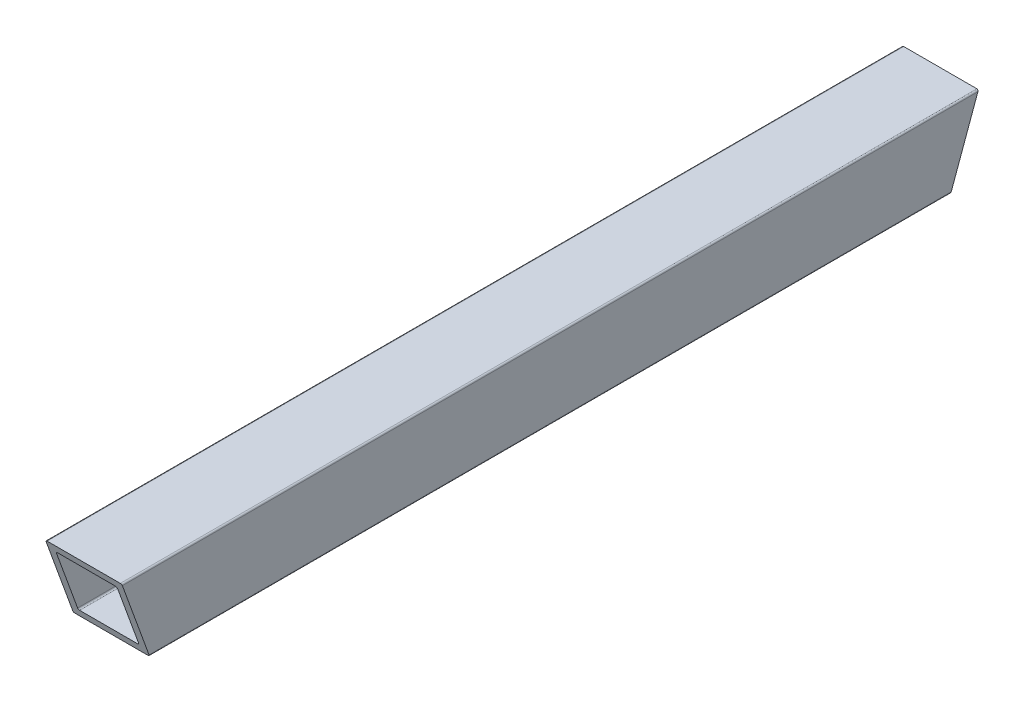
SolidWorks part; units mm, degrees
ref_plane "前基準面" through (0, 0, 0) normal (0, 0, 1) x (1, 0, 0)
ref_plane "上基準面" through (0, 0, 0) normal (0, 1, 0) x (1, 0, 0)
ref_plane "右基準面" through (0, 0, 0) normal (1, 0, 0) x (0, 0, -1)
sketch "草圖1" plane through (0, 0, 0) normal (0, 0, 1) x (1, 0, 0)
  line L1 (-5, 5) -> (5, 5)
  line L2 (-5, 5) -> (-5, -5)
  line L3 (-5, -5) -> (5, -5)
  line L4 (5, 5) -> (5, -5)
  line L5 (-4, 4) -> (4, 4)
  line L6 (-4, 4) -> (-4, -4)
  line L7 (-4, -4) -> (4, -4)
  line L8 (4, 4) -> (4, -4)
  dimension "D1" = 10
  dimension "D2" = 5
  dimension "D3" = 10
  dimension "D4" = 5
  dimension "D5" = 1
  dimension "D6" = 1
  dimension "D7" = 1
  dimension "D8" = 1
extrude "填料-伸長1" add sketch "草圖1" along normal blind 200
fillet "圓角1" radius 0.2 8 edges at (4, 4, 100) (-4, 4, 100) (-5, -5, 100) (4, -4, 100) (5, -5, 100) (-5, 5, 100) (-4, -4, 100) (5, 5, 100)
sketch "草圖2" plane through (5, 0, 0) normal (1, 0, 0) x (0, 0, -1)
  line L0 (0, 5) -> (0, -5)
  line L1 (0, -5) -> (-3.6397, -5)
  line L2 (0, -5) -> (-200, -5) construction
  line L3 (-3.6397, -5) -> (0, 5)
  dimension "D1" = 70
extrude "除料-伸長1" cut sketch "草圖2" against normal through all
sketch "草圖3" plane through (5, 0, 0) normal (1, 0, 0) x (0, 0, -1)
  line L0 (-108.6397, -5) -> (-112.2794, 5)
  line L1 (-3.6397, -5) -> (-200, -5) construction
  line L2 (-200, 5) -> (0, 5) construction
  line L3 (-112.2794, 5) -> (-200, 5)
  line L4 (-200, 5) -> (-200, -5)
  line L5 (-200, -5) -> (-108.6397, -5)
  dimension "D1" = 70
  dimension "D2" = 105
extrude "除料-伸長2" cut sketch "草圖3" against normal through all
